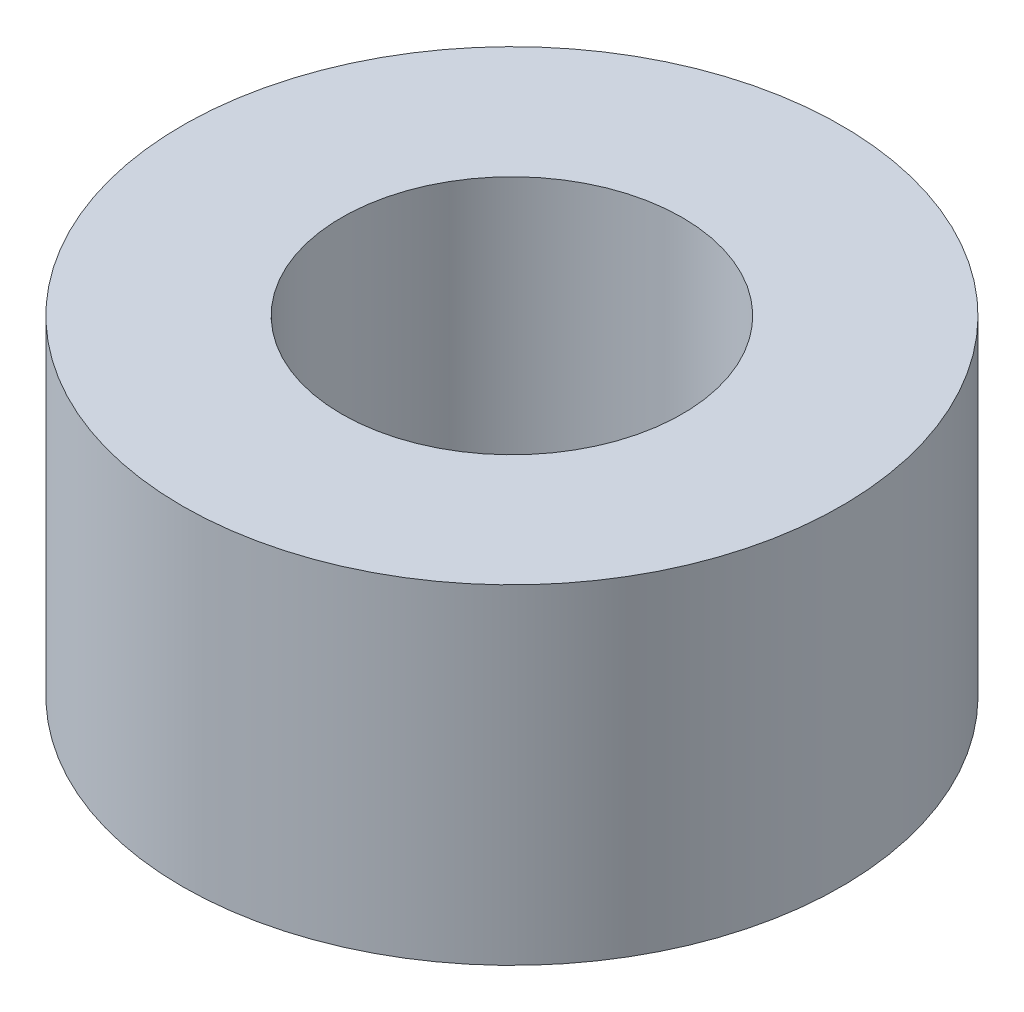
SolidWorks part; units mm, degrees
ref_plane "Front Plane" through (0, 0, 0) normal (0, 0, 1) x (1, 0, 0)
ref_plane "Top Plane" through (0, 0, 0) normal (0, 1, 0) x (1, 0, 0)
ref_plane "Right Plane" through (0, 0, 0) normal (1, 0, 0) x (0, 0, -1)
sketch "Sketch1" plane through (0, 0, 0) normal (0, 1, 0) x (1, 0, 0)
  circle A0 centre (0, 0) radius 1.55
  circle A1 centre (0, 0) radius 3
  dimension "D1" = 3.1
  dimension "D2" = 6
extrude "Boss-Extrude1" add sketch "Sketch1" along normal blind 3
